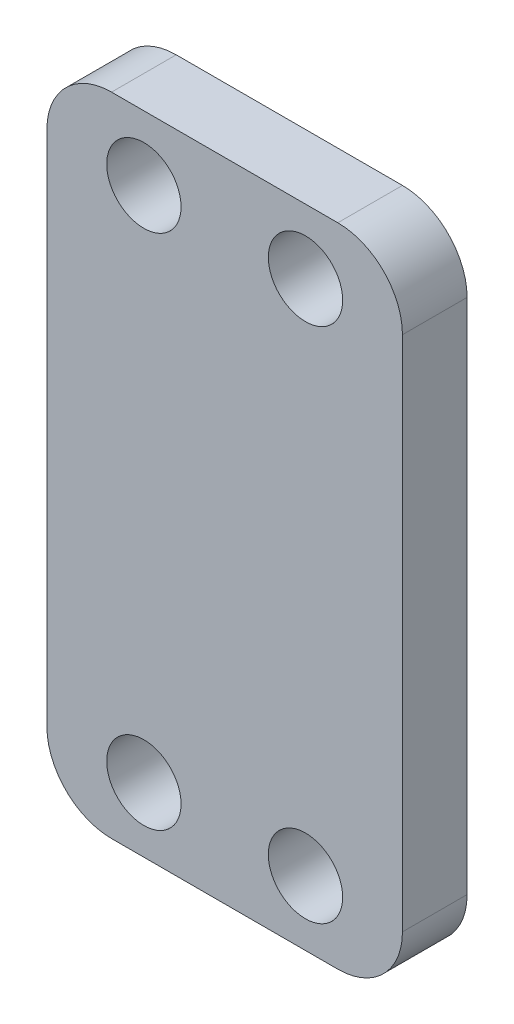
SolidWorks part; units mm, degrees
ref_plane "前视基准面" through (0, 0, 0) normal (0, 0, 1) x (1, 0, 0)
ref_plane "上视基准面" through (0, 0, 0) normal (0, 1, 0) x (1, 0, 0)
ref_plane "右视基准面" through (0, 0, 0) normal (1, 0, 0) x (0, 0, -1)
sketch "草图1" plane through (0, 0, 0) normal (0, 0, 1) x (1, 0, 0)
  line L1 (-5.5, -10) -> (5.5, -10)
  line L2 (-5.5, -10) -> (-5.5, 10)
  line L3 (-5.5, 10) -> (5.5, 10)
  line L4 (5.5, -10) -> (5.5, 10)
  line L5 (-5.5, -10) -> (5.5, 10) construction
  line L6 (-5.5, 10) -> (5.5, -10) construction
  point P0 (0, 0)
  dimension "D1" = 11
  dimension "D2" = 20
extrude "凸台-拉伸1" add sketch "草图1" along normal mid plane 2
sketch "草图2" plane through (0, 0, 1) normal (0, 0, 1) x (1, 0, 0)
  line L1 (-2.5, -8) -> (2.5, -8) construction
  line L2 (-2.5, -8) -> (-2.5, 8) construction
  line L3 (-2.5, 8) -> (2.5, 8) construction
  line L4 (2.5, -8) -> (2.5, 8) construction
  line L5 (-2.5, -8) -> (2.5, 8) construction
  line L6 (-2.5, 8) -> (2.5, -8) construction
  circle A1 centre (-2.5, 8) radius 1.15
  circle A2 centre (2.5, 8) radius 1.15
  circle A3 centre (-2.5, -8) radius 1.15
  circle A4 centre (2.5, -8) radius 1.15
  point P0 (0, 0)
  dimension "D1" = 2.3
  dimension "D3" = 5
  dimension "D2" = 16
extrude "切除-拉伸1" cut sketch "草图2" against normal through all
fillet "圆角1" radius 2 4 edges at (-5.5, -10, 0) (5.5, -10, 0) (5.5, 10, 0) (-5.5, 10, 0)
